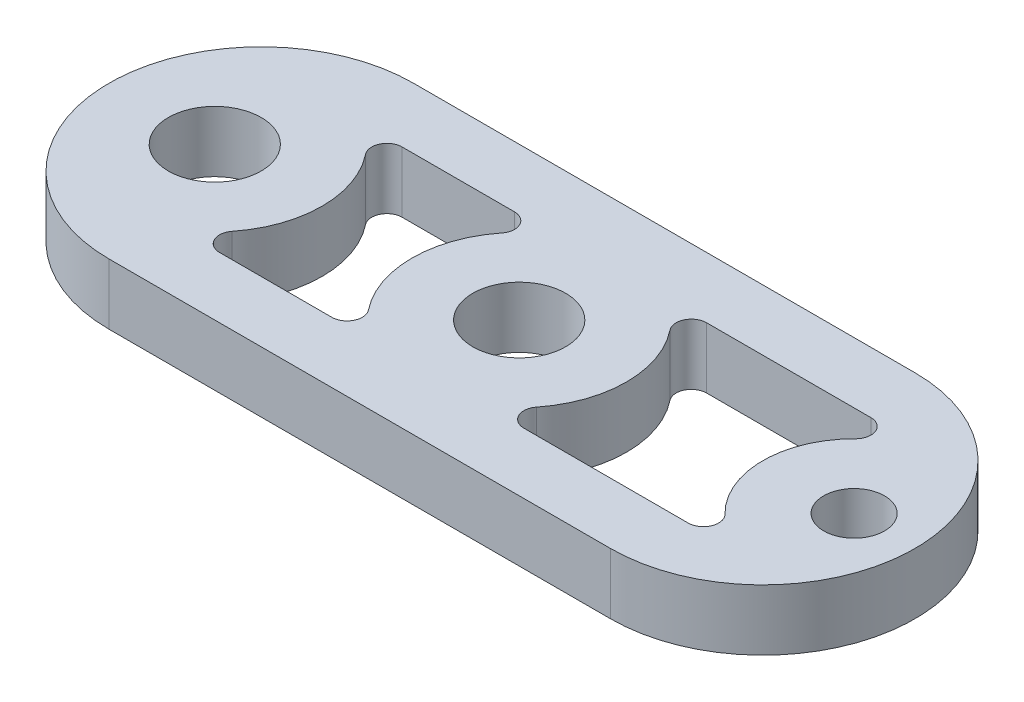
SolidWorks part; units mm, degrees
ref_plane "Front Plane" through (0, 0, 0) normal (0, 0, 1) x (1, 0, 0)
ref_plane "Top Plane" through (0, 0, 0) normal (0, 1, 0) x (1, 0, 0)
ref_plane "Right Plane" through (0, 0, 0) normal (1, 0, 0) x (0, 0, -1)
sketch "Sketch1" plane through (0, 0, 0) normal (0, 1, 0) x (1, 0, 0)
  line L0 (36, 0) -> (46, 0) construction
  line L1 (26.3089, -6) -> (37.101, -6)
  line L2 (26.3089, 6) -> (37.101, 6)
  line L3 (30, 10) -> (30, -10) construction
  line L4 (3.05, 10) -> (36, 10)
  line L5 (3.05, -10) -> (36, -10)
  line L9 (6.3089, 6) -> (13.6911, 6)
  line L10 (6.3089, -6) -> (13.6911, -6)
  circle A0 centre (42, 0) radius 2
  arc A1 (3.05, 10) -> (3.05, -10) centre (3.05, 0) ccw
  arc A3 (14.4748, 4.3789) -> (14.4748, -4.3789) centre (20, 0) ccw
  circle A4 centre (20, 0) radius 2 construction
  arc A6 (5.5252, -4.3789) -> (5.5252, 4.3789) centre (0, 0) ccw
  arc A7 (36, -10) -> (36, 10) centre (36, 0) ccw
  arc A8 (37.8009, 4.2857) -> (37.8009, -4.2857) centre (42, 0) ccw
  arc A9 (25.5252, -4.3789) -> (25.5252, 4.3789) centre (20, 0) ccw
  circle A10 centre (0, 0) radius 2 construction
  arc A12 (37.101, 6) -> (37.8009, 4.2857) centre (37.101, 5) cw
  arc A14 (37.101, -6) -> (37.8009, -4.2857) centre (37.101, -5) ccw
  arc A15 (26.3089, -6) -> (25.5252, -4.3789) centre (26.3089, -5) cw
  arc A17 (26.3089, 6) -> (25.5252, 4.3789) centre (26.3089, 5) ccw
  arc A20 (6.3089, 6) -> (5.5252, 4.3789) centre (6.3089, 5) ccw
  arc A21 (6.3089, -6) -> (5.5252, -4.3789) centre (6.3089, -5) cw
  arc A22 (13.6911, -6) -> (14.4748, -4.3789) centre (13.6911, -5) ccw
  arc A23 (13.6911, 6) -> (14.4748, 4.3789) centre (13.6911, 5) cw
  circle A24 centre (0, 0) radius 3.05
  circle A25 centre (20, 0) radius 3.05
  point P25 (36, -6)
  point P35 (0, 6)
  point P37 (0, -6)
  point P38 (26, -6)
  point P41 (14, 6)
  point P64 (18.6774, -5.8524)
  point P65 (4.984, -6)
  dimension "D1" = 1
extrude "Boss-Extrude1" add sketch "Sketch1" along normal blind 4
